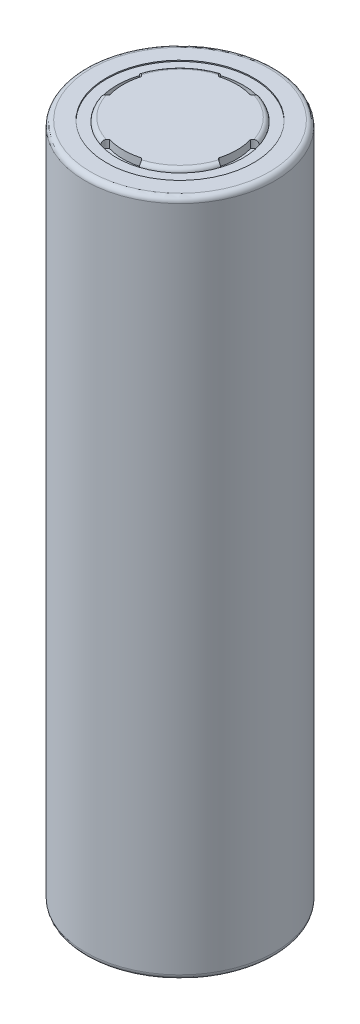
SolidWorks part; units mm, degrees
ref_plane "Plano frontal" through (0, 0, 0) normal (0, 0, 1) x (1, 0, 0)
ref_plane "Plano superior" through (0, 0, 0) normal (0, 1, 0) x (1, 0, 0)
ref_plane "Plano direito" through (0, 0, 0) normal (1, 0, 0) x (0, 0, -1)
sketch "Esboço1" plane through (0, 0, 0) normal (0, 1, 0) x (1, 0, 0)
  circle A0 centre (0, 0) radius 9
  dimension "D1" = 18
extrude "Ressalto-extrusão1" add sketch "Esboço1" along normal blind 64.5
sketch "Esboço3" plane through (0, 0, 0) normal (0, -1, 0) x (1, 0, 0)
  circle A2 centre (0, 0) radius 7
  circle A3 centre (0, 0) radius 7
  dimension "D1" = 2
extrude "Corte-extrusão1" cut sketch "Esboço3" against normal blind 0.5
sketch "Esboço4" plane through (0, 0.5, 0) normal (0, -1, 0) x (1, 0, 0)
  circle A0 centre (0, 0) radius 7
extrude "Ressalto-extrusão2" add sketch "Esboço4" along normal blind 0.75 separate body
fillet "Filete2" radius 0.5 1 edges at (0, -0.25, -7)
sketch "Esboço5" plane through (0, 64.5, 0) normal (0, 1, 0) x (1, 0, 0)
  circle A2 centre (0, 0) radius 7
  circle A3 centre (0, 0) radius 7
  dimension "D1" = 2
extrude "Corte-extrusão2" cut sketch "Esboço5" against normal blind 0.5
sketch "Esboço6" plane through (0, 64, 0) normal (0, 1, 0) x (1, 0, 0)
  circle A2 centre (0, 0) radius 6
  circle A3 centre (0, 0) radius 6
  circle A5 centre (0, 0) radius 7
  circle A6 centre (0, 0) radius 7
  dimension "D1" = 1
  dimension "D2" = 0
extrude "Ressalto-extrusão3" add sketch "Esboço6" along normal offset from surface (0.4 mm away) 0.1 separate body up to face at (0, 64.5, 7)
sketch "Esboço7" plane through (0, 64, 0) normal (0, 1, 0) x (1, 0, 0)
  circle A0 centre (0, 0) radius 6
extrude "Ressalto-extrusão4" add sketch "Esboço7" along normal blind 0.75 separate body
fillet "Filete3" radius 0.4 1 edges at (0, 64.75, 6)
fillet "Filete4" radius 0.5 2 edges at (0, 0, 9) (0, 64.5, 9)
sketch "Esboço8" plane through (0, 64.75, 0) normal (0, 1, 0) x (1, 0, 0)
  line L0 (0, 10.6267) -> (0, -11.1311) construction
  arc A0 (-1.8353, 5.7124) -> (-1.5026, 5.1867) centre (-1.1255, 5.7935) ccw
  circle A1 centre (0, 0) radius 6 construction
  arc A4 (-1.8353, 5.7124) -> (1.8353, 5.7124) centre (0, 0) cw
  arc A5 (1.8353, 5.7124) -> (1.5026, 5.1867) centre (1.1255, 5.7935) cw
  arc A6 (-1.5026, 5.1867) -> (1.5026, 5.1867) centre (0, 0) cw
  arc A7 (5.7124, -1.8353) -> (5.1867, -1.5026) centre (5.7935, -1.1255) cw
  arc A8 (5.7124, 1.8353) -> (5.7124, -1.8353) centre (0, 0) cw
  arc A9 (5.7124, 1.8353) -> (5.1867, 1.5026) centre (5.7935, 1.1255) ccw
  arc A10 (5.1867, 1.5026) -> (5.1867, -1.5026) centre (0, 0) cw
  arc A11 (-1.8353, -5.7124) -> (-1.5026, -5.1867) centre (-1.1255, -5.7935) cw
  arc A12 (1.8353, -5.7124) -> (-1.8353, -5.7124) centre (0, 0) cw
  arc A13 (1.8353, -5.7124) -> (1.5026, -5.1867) centre (1.1255, -5.7935) ccw
  arc A14 (1.5026, -5.1867) -> (-1.5026, -5.1867) centre (0, 0) cw
  arc A15 (-5.7124, 1.8353) -> (-5.1867, 1.5026) centre (-5.7935, 1.1255) cw
  arc A16 (-5.7124, -1.8353) -> (-5.7124, 1.8353) centre (0, 0) cw
  arc A17 (-5.7124, -1.8353) -> (-5.1867, -1.5026) centre (-5.7935, -1.1255) ccw
  arc A18 (-5.1867, -1.5026) -> (-5.1867, 1.5026) centre (0, 0) cw
  point P34 (0, 0)
  dimension "D1" = 4
extrude "Corte-extrusão3" cut sketch "Esboço8" against normal blind 0.75
